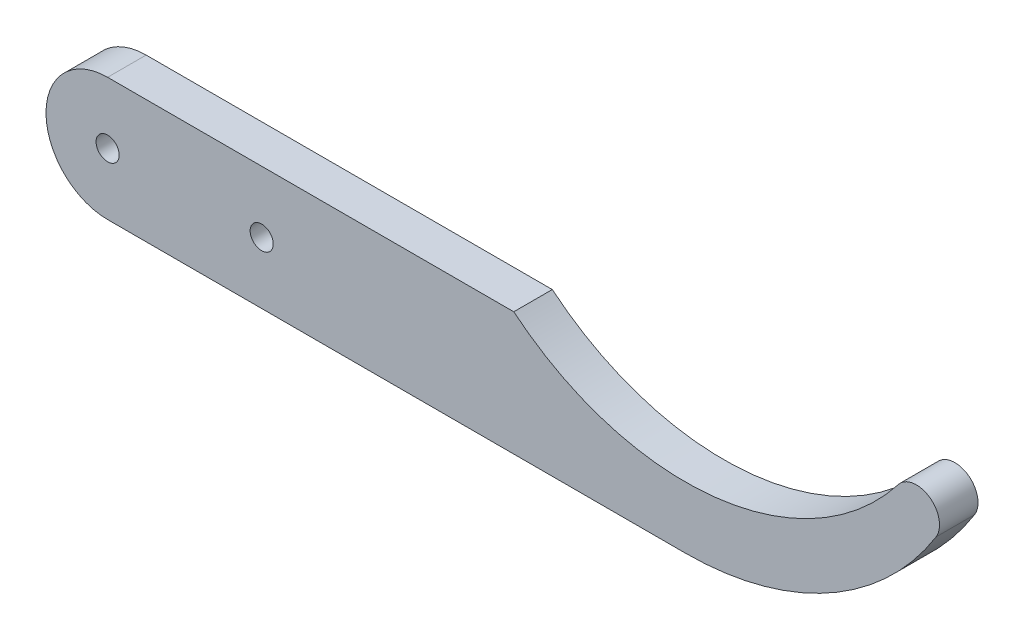
SolidWorks part; units mm, degrees
ref_plane "Plan de face" through (0, 0, 0) normal (0, 0, 1) x (1, 0, 0)
ref_plane "Plan de dessus" through (0, 0, 0) normal (0, 1, 0) x (1, 0, 0)
ref_plane "Plan de droite" through (0, 0, 0) normal (1, 0, 0) x (0, 0, -1)
sketch "Esquisse1" plane through (0, 0, 0) normal (0, 0, 1) x (1, 0, 0)
  line L0 (0, 0) -> (80, 0) construction
  line L1 (20, 0) -> (20, 23.8674) construction
  line L2 (0, 0) -> (0, 35) construction
  line L3 (0, 35) -> (55, 35) construction
  line L4 (0, 8) -> (20, 8)
  line L5 (82.6316, 13.5175) -> (85, 11.6762) construction
  line L6 (20, 8) -> (32.7289, 8)
  line L7 (0, -8) -> (55, -8)
  line L8 (55, 35) -> (55, -8) construction
  line L9 (0, 8) -> (-20, 8)
  line L10 (0, 0) -> (-20, 0) construction
  line L11 (0, -8) -> (-20, -8)
  circle A0 centre (0, 0) radius 1.5
  arc A1 (0, -8) -> (0, 8) centre (0, 0) cw construction
  circle A2 centre (55, 35) radius 35 construction
  arc A3 (32.7289, 8) -> (82.6316, 13.5175) centre (55, 35) ccw
  arc A4 (82.6316, 13.5175) -> (87.5479, 10.0925) centre (85, 11.6762) cw
  arc A5 (55, -8) -> (87.5479, 10.0925) centre (55, 30.3227) ccw
  circle A6 centre (15, 0) radius 1.5 construction
  arc A7 (-20, 8) -> (-20, -8) centre (-20, 0) ccw
  circle A8 centre (-20, 0) radius 1.5
  dimension "D3" = 3
  dimension "D4" = 35
  dimension "D6" = 70
  dimension "D7" = 3
  dimension "D8" = 8
  dimension "D9" = 30
  dimension "D10" = 15
  dimension "D11" = 8
  dimension "D1" = 20
  dimension "D2" = 80
  dimension "D5" = 55
  dimension "D12" = 20
extrude "Boss.-Extru.1" add sketch "Esquisse1" along normal blind 5
